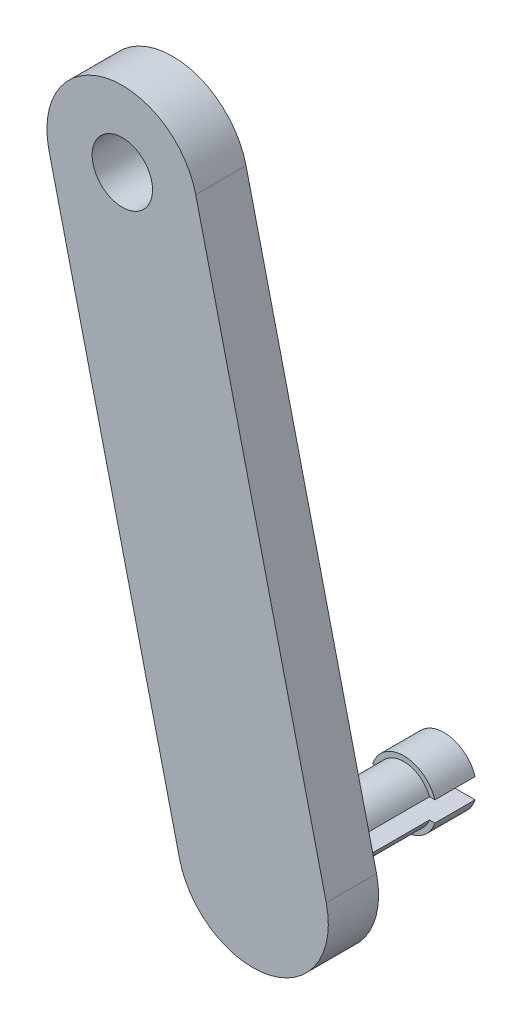
SolidWorks part; units mm, degrees
ref_plane "Plan de face" through (0, 0, 0) normal (0, 0, 1) x (1, 0, 0)
ref_plane "Plan de dessus" through (0, 0, 0) normal (0, 1, 0) x (1, 0, 0)
ref_plane "Plan de droite" through (0, 0, 0) normal (1, 0, 0) x (0, 0, -1)
sketch "Esquisse1" plane through (0, 0, 0) normal (0, 0, 1) x (1, 0, 0)
  line L0 (-64, -4) -> (-51.0249, -58.4761) construction
  line L1 (-56.7041, -2.2623) -> (-43.729, -56.7384)
  line L2 (-71.2959, -5.7377) -> (-58.3209, -60.2139)
  arc A0 (-56.7041, -2.2623) -> (-71.2959, -5.7377) centre (-64, -4) ccw
  arc A1 (-58.3209, -60.2139) -> (-43.729, -56.7384) centre (-51.0249, -58.4761) ccw
  point P4 (-57.5125, -31.2381)
  dimension "D1" = 15
extrude "Boss.-Extru.1" add sketch "Esquisse1" along normal blind 5
sketch "Esquisse2" plane through (0, 0, 5) normal (0, 0, 1) x (1, 0, 0)
  circle A0 centre (-51.0249, -58.4761) radius 2.75
  dimension "D1" = 5.5
extrude "Boss.-Extru.2" add sketch "Esquisse2" against normal blind 15
sketch "Esquisse4" plane through (0, 0, -10) normal (0, 0, -1) x (-1, 0, 0)
  circle A0 centre (51.0249, -58.4761) radius 3.25
  dimension "D1" = 6.5
extrude "Boss.-Extru.3" add sketch "Esquisse4" along normal blind 4
sketch "Esquisse5" plane through (0, 0, -14) normal (0, 0, -1) x (-1, 0, 0)
  line L1 (46.0249, -57.4761) -> (56.0249, -57.4761)
  line L2 (46.0249, -57.4761) -> (46.0249, -59.4761)
  line L3 (46.0249, -59.4761) -> (56.0249, -59.4761)
  line L4 (56.0249, -57.4761) -> (56.0249, -59.4761)
  dimension "D1" = 1
  dimension "D2" = 1
  dimension "D3" = 5
  dimension "D4" = 10
extrude "Enlèv. mat.-Extru.2" cut sketch "Esquisse5" against normal blind 14
sketch "Esquisse6" plane through (0, 0, 5) normal (0, 0, 1) x (1, 0, 0)
  circle A0 centre (-64, -4) radius 3
  dimension "D1" = 6
extrude "Enlèv. mat.-Extru.3" cut sketch "Esquisse6" against normal blind 14
